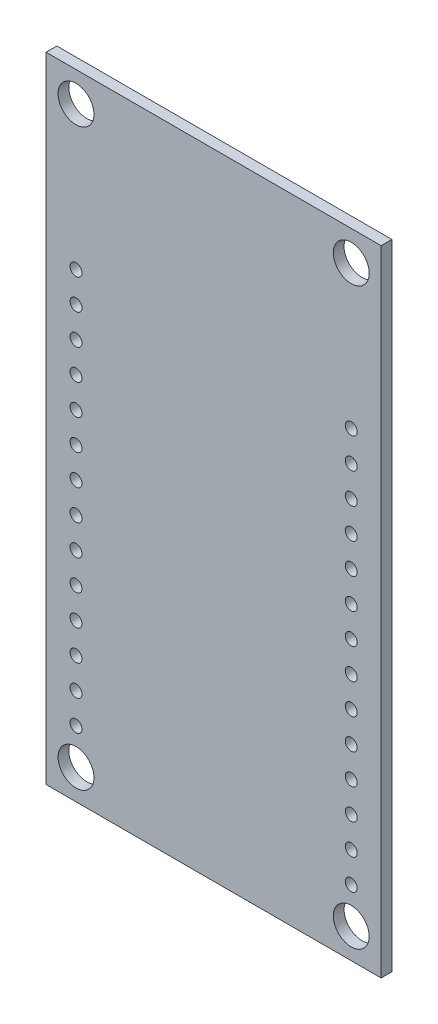
SolidWorks part; units mm, degrees
ref_plane "Plano frontal" through (0, 0, 0) normal (0, 0, 1) x (1, 0, 0)
ref_plane "Plano superior" through (0, 0, 0) normal (0, 1, 0) x (1, 0, 0)
ref_plane "Plano direito" through (0, 0, 0) normal (1, 0, 0) x (0, 0, -1)
sketch "Esboço1" plane through (0, 0, 0) normal (0, 0, 1) x (1, 0, 0)
  line L1 (14, -26.5) -> (-14, -26.5)
  line L2 (14, -26.5) -> (14, 26.5)
  line L3 (14, 26.5) -> (-14, 26.5)
  line L4 (-14, -26.5) -> (-14, 26.5)
  line L5 (14, -26.5) -> (-14, 26.5) construction
  line L6 (14, 26.5) -> (-14, -26.5) construction
  point P0 (0, 0)
  dimension "D1" = 28
  dimension "D2" = 53
extrude "Ressalto-extrusão1" add sketch "Esboço1" along normal mid plane 0.9
sketch "Esboço4" plane through (0, 0, 0.45) normal (0, 0, 1) x (1, 0, 0)
  line L0 (-14, 26.5) -> (-14, -26.5) construction
  line L1 (-14, -26.5) -> (14, -26.5) construction
  line L2 (0, -0.495) -> (0, 0.495) construction
  line L3 (0.495, 0) -> (-0.495, 0) construction
  circle A0 centre (-11.5, -24) radius 1.5
  circle A1 centre (11.5, -24) radius 1.5
  circle A2 centre (11.5, 24) radius 1.5
  circle A3 centre (-11.5, 24) radius 1.5
  dimension "D1" = 3
  dimension "D2" = 2.5
  dimension "D3" = 2.5
extrude "Corte-extrusão1" cut sketch "Esboço4" against normal up to next
sketch "Esboço5" plane through (0, 0, 0.45) normal (0, 0, 1) x (1, 0, 0)
  line L0 (-11.5, -24) -> (-11.5, 24) construction
  line L1 (0, -0.495) -> (0, 0.495) construction
  circle A0 centre (-11.5, -21) radius 0.5
  circle A16 centre (-11.5, -24) radius 1.5 construction
  circle A30 centre (11.5, -21) radius 0.5
  point P68 (0, 0)
  dimension "D2" = 1
  dimension "D1" = 3
extrude "Corte-extrusão2" cut sketch "Esboço5" against normal up to next
pattern_linear "Padrão linear1" count 14 spacing 2.54 along (0, 1, 0) of "Corte-extrusão2"
